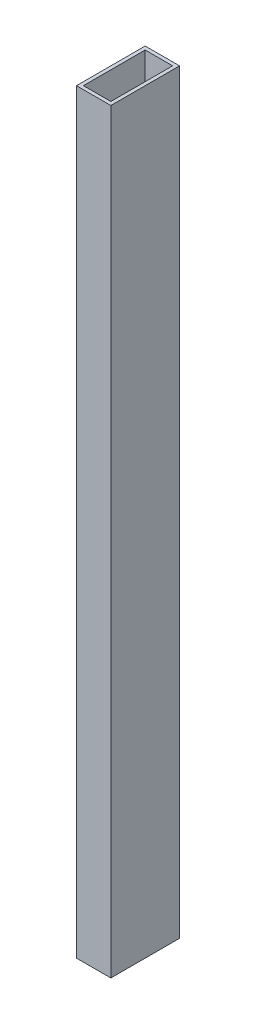
SolidWorks part; units mm, degrees
ref_plane "Front Plane" through (0, 0, 0) normal (0, 0, 1) x (1, 0, 0)
ref_plane "Top Plane" through (0, 0, 0) normal (0, 1, 0) x (1, 0, 0)
ref_plane "Right Plane" through (0, 0, 0) normal (1, 0, 0) x (0, 0, -1)
sketch "Sketch1" plane through (0, 0, 0) normal (0, 1, 0) x (1, 0, 0)
  line L1 (0, 0) -> (25.4, 0)
  line L2 (0, 0) -> (0, 50.8)
  line L3 (0, 50.8) -> (25.4, 50.8)
  line L4 (25.4, 0) -> (25.4, 50.8)
  dimension "D1" = 25.4
  dimension "D2" = 50.8
extrude "Boss-Extrude2" add sketch "Sketch1" along normal blind 558.8 contours L2 L3 L4 L1
sketch "Sketch2" plane through (0, 558.8, 0) normal (0, 1, 0) x (1, 0, 0)
  line L0 (12.7, 50.8) -> (12.7, 0) construction
  line L1 (0, 50.8) -> (25.4, 50.8) construction
  line L2 (0, 0) -> (25.4, 0) construction
  line L3 (0, 25.4) -> (25.4, 25.4) construction
  line L4 (0, 0) -> (0, 50.8) construction
  line L5 (25.4, 0) -> (25.4, 50.8) construction
  line L6 (25.4, 25.4) -> (22.86, 25.4) construction
  line L7 (12.7, 0) -> (12.7, 2.54) construction
  line L9 (2.54, 48.26) -> (22.86, 48.26)
  line L10 (2.54, 48.26) -> (2.54, 2.54)
  line L11 (2.54, 2.54) -> (22.86, 2.54)
  line L12 (22.86, 48.26) -> (22.86, 2.54)
  line L13 (2.54, 48.26) -> (22.86, 2.54) construction
  line L14 (2.54, 2.54) -> (22.86, 48.26) construction
  point P14 (12.7, 25.4)
extrude "Cut-Extrude1" cut sketch "Sketch2" against normal blind 558.8 contours L10 L11 L12 L9
